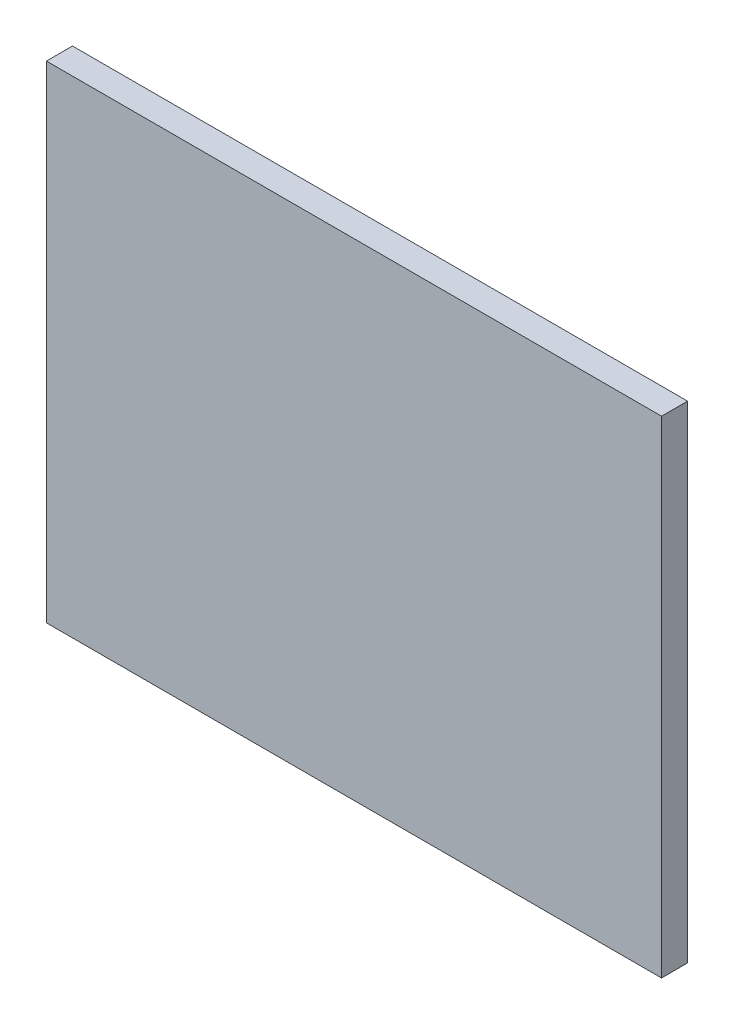
SolidWorks part; units mm, degrees
ref_plane "Plan de face" through (0, 0, 0) normal (0, 0, 1) x (1, 0, 0)
ref_plane "Plan de dessus" through (0, 0, 0) normal (0, 1, 0) x (1, 0, 0)
ref_plane "Plan de droite" through (0, 0, 0) normal (1, 0, 0) x (0, 0, -1)
sketch "Esquisse1" plane through (0, 0, 0) normal (0, 0, 1) x (1, 0, 0)
  line L1 (0, 0) -> (354, 0)
  line L2 (0, 0) -> (0, 280)
  line L3 (0, 280) -> (354, 280)
  line L4 (354, 0) -> (354, 280)
  dimension "D1" = 354
  dimension "D2" = 280
extrude "Boss.-Extru.1" add sketch "Esquisse1" along normal blind 15
